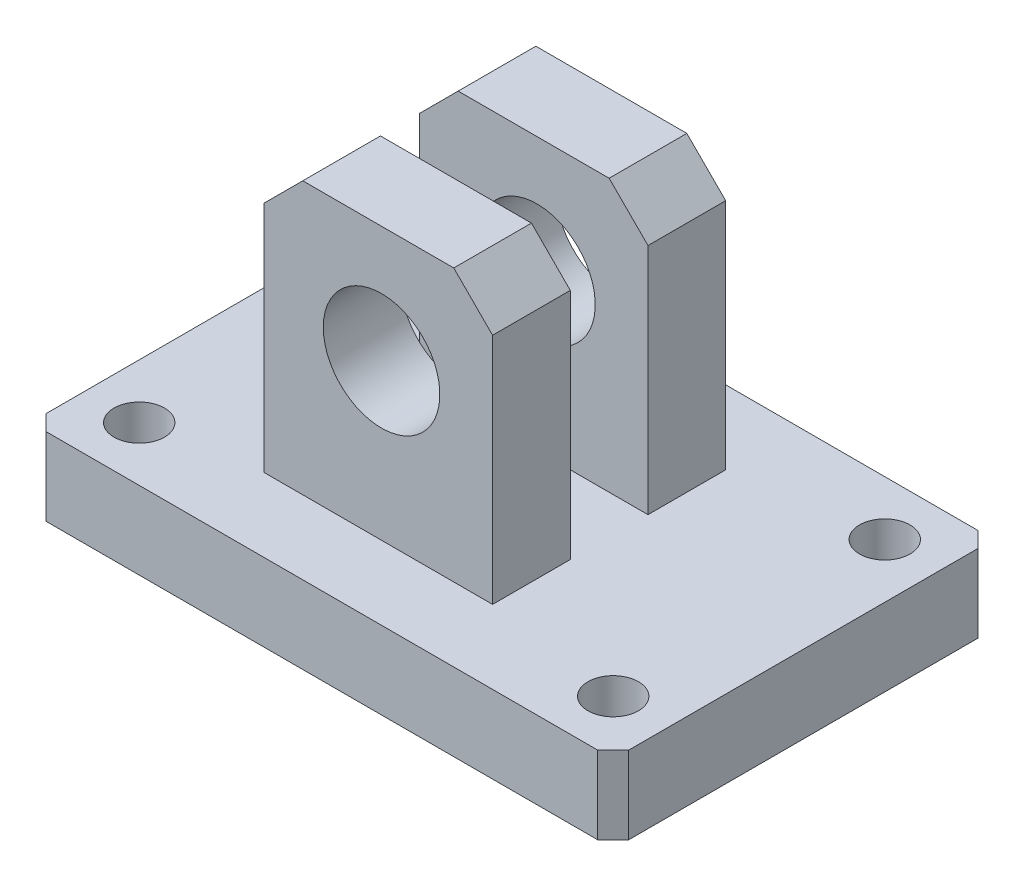
SolidWorks part; units mm, degrees
ref_plane "Front Plane" through (0, 0, 0) normal (0, 0, 1) x (1, 0, 0)
ref_plane "Top Plane" through (0, 0, 0) normal (0, 1, 0) x (1, 0, 0)
ref_plane "Right Plane" through (0, 0, 0) normal (1, 0, 0) x (0, 0, -1)
sketch "Sketch1" plane through (0, 0, 0) normal (0, 1, 0) x (1, 0, 0)
  line L0 (-66.9146, 0) -> (59.6243, 0) construction
  line L1 (-37.5, -22.4746) -> (-37.5, 22.4746)
  line L2 (-35.5, 24.4746) -> (35.5, 24.4746)
  line L3 (37.5, 22.4746) -> (37.5, -22.4746)
  line L4 (-37.5, 22.4746) -> (-35.5, 24.4746)
  line L5 (35.5, 24.4746) -> (37.5, 22.4746)
  line L6 (35.5, -24.4746) -> (37.5, -22.4746)
  line L7 (-37.5, -22.4746) -> (-35.5, -24.4746)
  line L8 (-35.5, -24.4746) -> (35.5, -24.4746)
  circle A0 centre (-30.5, 17.4746) radius 3.25
  circle A1 centre (30.5, 17.4746) radius 3.25
  circle A2 centre (30.5, -17.4746) radius 3.25
  circle A3 centre (-30.5, -17.4746) radius 3.25
  point P3 (37.5, -24.4746)
  point P4 (-37.5, 24.4746)
  point P5 (37.5, 24.4746)
  point P7 (-37.5, 0)
  point P23 (37.5, 0)
  point P24 (-37.5, -24.4746)
  dimension "D5" = 6.5
  dimension "D6" = 6.5
  dimension "D7" = 7
  dimension "D8" = 7
  dimension "D1" = 75
  dimension "D2" = 61
  dimension "D9" = 37.5
extrude "Boss-Extrude1" add sketch "Sketch1" along normal blind 10
sketch "Sketch2" plane through (0, 10, 0) normal (0, 1, 0) x (1, 0, 0)
  line L0 (-29.5873, 0) -> (29.8979, 0) construction
  line L1 (12.5028, -15) -> (12.5028, -5)
  line L2 (-16.9292, 15) -> (12.5028, 15)
  line L3 (-16.9292, 15) -> (-16.9292, 5)
  line L4 (-16.9292, 5) -> (12.5028, 5)
  line L5 (12.5028, 15) -> (12.5028, 5)
  line L6 (-16.9292, -5) -> (12.5028, -5)
  line L7 (-16.9292, -15) -> (-16.9292, -5)
  line L8 (-16.9292, -15) -> (12.5028, -15)
  dimension "D1" = 15
  dimension "D2" = 10
extrude "Boss-Extrude2" add sketch "Sketch2" along normal blind 35
sketch "Sketch3" plane through (0, 0, -15) normal (0, 0, -1) x (-1, 0, 0)
  line L0 (-35.5, 0) -> (35.5, 0) construction
  circle A0 centre (1.7861, 30) radius 7.5
  dimension "D1" = 15
  dimension "D2" = 30
extrude "Cut-Extrude1" cut sketch "Sketch3" against normal blind 35
chamfer "Chamfer1" distance 5 4 edges at (-16.9292, 45, 10) (12.5028, 45, 10) (-16.9292, 45, -10) (12.5028, 45, -10)
